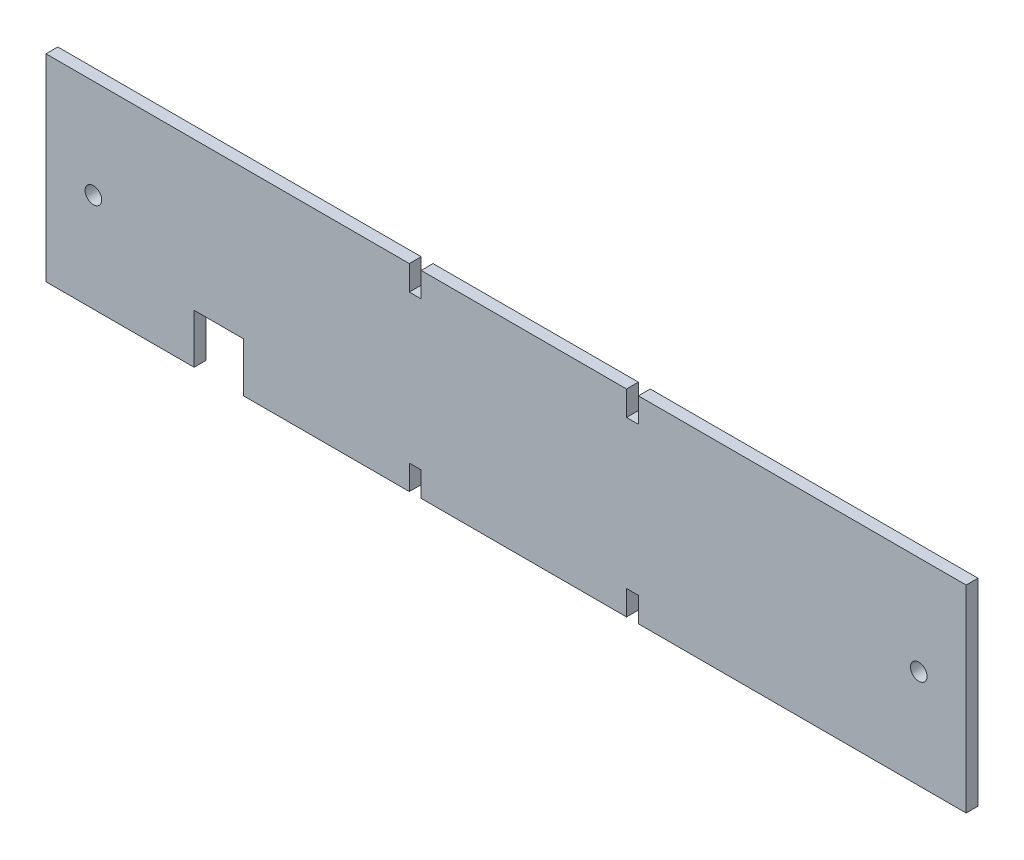
SolidWorks part; units mm, degrees
ref_plane "Front Plane" through (0, 0, 0) normal (0, 0, 1) x (1, 0, 0)
ref_plane "Top Plane" through (0, 0, 0) normal (0, 1, 0) x (1, 0, 0)
ref_plane "Right Plane" through (0, 0, 0) normal (1, 0, 0) x (0, 0, -1)
sketch "Sketch1" plane through (0, 0, 0) normal (0, 0, 1) x (1, 0, 0)
  line L1 (0, 0) -> (466, 0)
  line L2 (0, 0) -> (0, 100)
  line L3 (0, 100) -> (466, 100)
  line L4 (466, 0) -> (466, 100)
  dimension "D1" = 100
  dimension "D2" = 466
extrude "Boss-Extrude1" add sketch "Sketch1" along normal blind 6
hole_wizard "M8 Clearance Slot1" positions "Sketch2" profile "Sketch3" size "M8" standard "ANSI Metric" slot yes end condition through all
sketch "Sketch2" plane through (0, 0, 6) normal (0, 0, 1) x (1, 0, 0)
  line L0 (466, 100) -> (0, 100) construction
  line L1 (466, 0) -> (466, 100) construction
  line L2 (0, 100) -> (0, 0) construction
  point P0 (24, 50)
  point P2 (442, 50)
  dimension "D1" = 50
  dimension "D2" = 24
  dimension "D3" = 24
  dimension "D4" = 50
sketch "Sketch3" plane through (24, 50, 6) normal (1, 0, 0) x (0, -1, 0)
  line L0 (0, 0) -> (0, 6)
  line L1 (0, 6) -> (4.2, 6)
  line L2 (4.2, 6) -> (4.2, 0)
  line L5 (4.2, 0) -> (0, 0)
  line L11 (0, -6.35) -> (0, 107.95) construction
  dimension "Thru Hole Dia." = 8.4
  dimension "Thru Hole Depth" = 6
sketch "Sketch4" plane through (0, 0, 0) normal (0, 0, -1) x (-1, 0, 0)
  line L0 (0, 0) -> (-466, 0) construction
  line L1 (-75, 0) -> (-100, 0)
  line L2 (-75, 0) -> (-75, 25)
  line L3 (-75, 25) -> (-100, 25)
  line L4 (-100, 0) -> (-100, 25)
  line L5 (0, 100) -> (0, 0) construction
  dimension "D1" = 25
  dimension "D2" = 25
  dimension "D3" = 75
extrude "Cut-Extrude1" cut sketch "Sketch4" against normal blind 12
sketch "Sketch5" plane through (0, 0, 0) normal (0, 0, -1) x (-1, 0, 0)
  line L0 (-466, 100) -> (0, 100) construction
  line L1 (-300, 100) -> (-294, 100)
  line L2 (-300, 100) -> (-300, 87.5)
  line L3 (-300, 87.5) -> (-294, 87.5)
  line L4 (-294, 100) -> (-294, 87.5)
  line L5 (-466, 0) -> (-466, 100) construction
  line L6 (0, 100) -> (0, 0) construction
  line L7 (-184, 100) -> (-190, 100)
  line L8 (-184, 100) -> (-184, 87.5)
  line L9 (-184, 87.5) -> (-190, 87.5)
  line L10 (-190, 100) -> (-190, 87.5)
  line L11 (-100, 0) -> (-466, 0) construction
  line L12 (-300, 0) -> (-294, 0)
  line L13 (-300, 0) -> (-300, 12.5)
  line L14 (-300, 12.5) -> (-294, 12.5)
  line L15 (-294, 0) -> (-294, 12.5)
  line L17 (-190, 0) -> (-184, 0)
  line L18 (-190, 0) -> (-190, 12.5)
  line L19 (-190, 12.5) -> (-184, 12.5)
  line L20 (-184, 0) -> (-184, 12.5)
  dimension "D1" = 6
  dimension "D2" = 12.5
  dimension "D3" = 166
  dimension "D4" = 6
  dimension "D5" = 12.5
  dimension "D6" = 184
  dimension "D7" = 6
  dimension "D8" = 6
  dimension "D9" = 12.5
  dimension "D10" = 12.5
  dimension "D11" = 166
  dimension "D12" = 184
extrude "Cut-Extrude2" cut sketch "Sketch5" against normal through all
